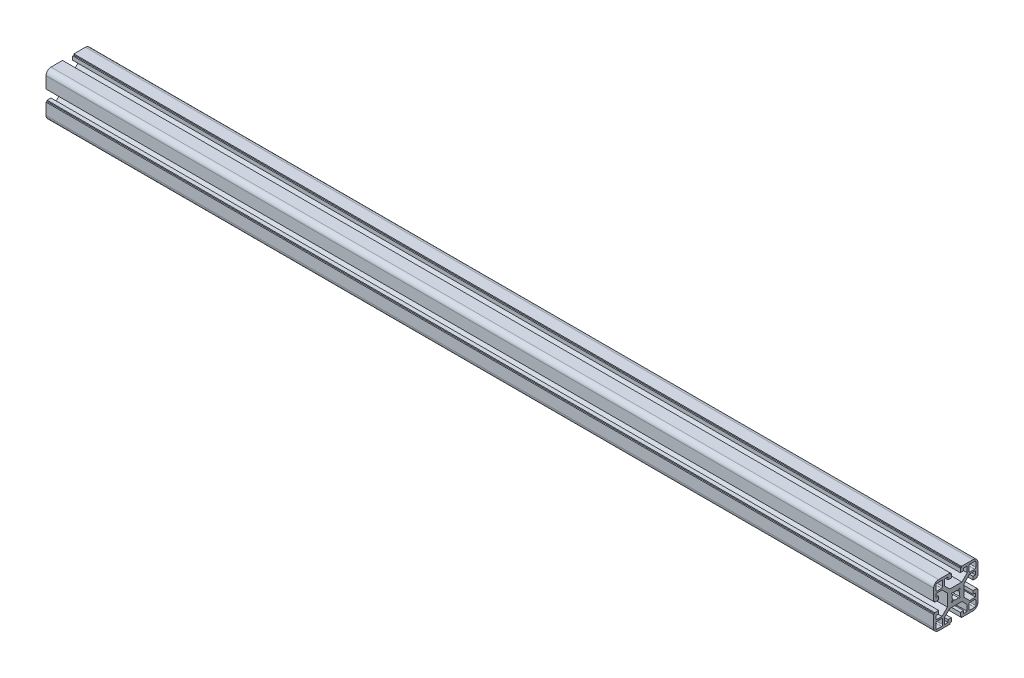
SolidWorks part; units mm, degrees
ref_plane "前视基准面" through (0, 0, 0) normal (0, 0, 1) x (1, 0, 0)
ref_plane "上视基准面" through (0, 0, 0) normal (0, 1, 0) x (1, 0, 0)
ref_plane "右视基准面" through (0, 0, 0) normal (1, 0, 0) x (0, 0, -1)
other "Configuration Table"
sketch "草图1" plane through (0, 0, 0) normal (1, 0, 0) x (0, 0, -1)
  line L0 (4.82, 19.28) -> (3.82, 19.28)
  line L1 (3.82, 19.28) -> (3.82, 15.78)
  line L2 (3.82, 15.78) -> (6.7364, 15.78)
  line L3 (6.7364, 15.78) -> (6.7364, 18.03)
  line L4 (6.7364, 18.03) -> (10.02, 18.03)
  line L5 (10.02, 18.03) -> (10.02, 12.7013)
  line L6 (10.02, 12.7013) -> (5.1987, 7.88)
  line L7 (5.1987, 7.88) -> (-5.7586, 7.88)
  line L8 (-5.7586, 7.88) -> (-10.58, 12.7013)
  line L9 (-10.58, 12.7013) -> (-10.58, 18.03)
  line L10 (-10.58, 18.03) -> (-7.2963, 18.03)
  line L11 (-7.2963, 18.03) -> (-7.2963, 15.78)
  line L12 (-7.2963, 15.78) -> (-4.38, 15.78)
  line L13 (-4.38, 15.78) -> (-4.38, 19.28)
  line L14 (-4.38, 19.28) -> (-5.38, 19.28)
  line L15 (-5.38, 19.28) -> (-5.38, 20.28)
  line L16 (-5.38, 20.28) -> (-15.78, 20.28)
  line L17 (-20.28, 15.78) -> (-20.28, 5.38)
  line L18 (-20.28, 5.38) -> (-19.28, 5.38)
  line L19 (-19.28, 5.38) -> (-19.28, 4.38)
  line L20 (-19.28, 4.38) -> (-15.78, 4.38)
  line L21 (-15.78, 4.38) -> (-15.78, 7.2963)
  line L22 (-15.78, 7.2963) -> (-18.03, 7.2963)
  line L23 (-18.03, 7.2963) -> (-18.03, 10.58)
  line L24 (-18.03, 10.58) -> (-12.7013, 10.58)
  line L25 (-12.7013, 10.58) -> (-7.88, 5.7586)
  line L26 (-7.88, 5.7586) -> (-7.88, -5.1987)
  line L27 (-7.88, -5.1987) -> (-12.7013, -10.02)
  line L28 (-12.7013, -10.02) -> (-18.03, -10.02)
  line L29 (-18.03, -10.02) -> (-18.03, -6.7364)
  line L30 (-18.03, -6.7364) -> (-15.78, -6.7364)
  line L31 (-15.78, -6.7364) -> (-15.78, -3.82)
  line L32 (-15.78, -3.82) -> (-19.28, -3.82)
  line L33 (-19.28, -3.82) -> (-19.28, -4.82)
  line L34 (-19.28, -4.82) -> (-20.28, -4.82)
  line L35 (-20.28, -4.82) -> (-20.28, -15.22)
  line L36 (-15.78, -19.72) -> (-5.38, -19.72)
  line L37 (-5.38, -19.72) -> (-5.38, -18.72)
  line L38 (-5.38, -18.72) -> (-4.38, -18.72)
  line L39 (-4.38, -18.72) -> (-4.38, -15.22)
  line L40 (-4.38, -15.22) -> (-7.2963, -15.22)
  line L41 (-7.2963, -15.22) -> (-7.2963, -17.47)
  line L42 (-7.2963, -17.47) -> (-10.58, -17.47)
  line L43 (-10.58, -17.47) -> (-10.58, -12.1414)
  line L44 (-10.58, -12.1414) -> (-5.7586, -7.32)
  line L45 (-5.7586, -7.32) -> (5.1987, -7.32)
  line L46 (5.1987, -7.32) -> (10.02, -12.1414)
  line L47 (10.02, -12.1414) -> (10.02, -17.47)
  line L48 (10.02, -17.47) -> (6.7364, -17.47)
  line L49 (6.7364, -17.47) -> (6.7364, -15.22)
  line L50 (6.7364, -15.22) -> (3.82, -15.22)
  line L51 (3.82, -15.22) -> (3.82, -18.72)
  line L52 (3.82, -18.72) -> (4.82, -18.72)
  line L53 (4.82, -18.72) -> (4.82, -19.72)
  line L54 (4.82, -19.72) -> (15.22, -19.72)
  line L55 (19.72, -15.22) -> (19.72, -4.82)
  line L56 (19.72, -4.82) -> (18.72, -4.82)
  line L57 (18.72, -4.82) -> (18.72, -3.82)
  line L58 (18.72, -3.82) -> (15.22, -3.82)
  line L59 (15.22, -3.82) -> (15.22, -6.7364)
  line L60 (15.22, -6.7364) -> (17.47, -6.7364)
  line L61 (17.47, -6.7364) -> (17.47, -10.02)
  line L62 (17.47, -10.02) -> (12.1414, -10.02)
  line L63 (12.1414, -10.02) -> (7.32, -5.1987)
  line L64 (7.32, -5.1987) -> (7.32, 5.7586)
  line L65 (7.32, 5.7586) -> (12.1414, 10.58)
  line L66 (12.1414, 10.58) -> (17.47, 10.58)
  line L67 (17.47, 10.58) -> (17.47, 7.2963)
  line L68 (17.47, 7.2963) -> (15.22, 7.2963)
  line L69 (15.22, 7.2963) -> (15.22, 4.38)
  line L70 (15.22, 4.38) -> (18.72, 4.38)
  line L71 (18.72, 4.38) -> (18.72, 5.38)
  line L72 (18.72, 5.38) -> (19.72, 5.38)
  line L73 (19.72, 5.38) -> (19.72, 15.78)
  line L74 (15.22, 20.28) -> (4.82, 20.28)
  line L75 (4.82, 20.28) -> (4.82, 19.28)
  line L76 (-13.08, -17.72) -> (-17.28, -17.72)
  line L77 (-18.28, -16.72) -> (-18.28, -12.52)
  line L78 (-17.28, -11.52) -> (-13.08, -11.52)
  line L79 (-12.08, -12.52) -> (-12.08, -16.72)
  line L80 (-17.28, 18.28) -> (-13.08, 18.28)
  line L81 (-12.08, 17.28) -> (-12.08, 13.08)
  line L82 (-13.08, 12.08) -> (-17.28, 12.08)
  line L83 (-18.28, 13.08) -> (-18.28, 17.28)
  line L84 (16.72, 12.08) -> (12.52, 12.08)
  line L85 (11.52, 13.08) -> (11.52, 17.28)
  line L86 (12.52, 18.28) -> (16.72, 18.28)
  line L87 (17.72, 17.28) -> (17.72, 13.08)
  line L88 (3.7505, -3.0434) -> (3.0434, -3.7505)
  line L89 (3.0434, -3.7505) -> (1.7445, -2.4516)
  line L90 (-2.3044, -2.4516) -> (-3.6033, -3.7505)
  line L91 (-3.6033, -3.7505) -> (-4.3104, -3.0434)
  line L92 (-4.3104, -3.0434) -> (-3.0115, -1.7445)
  line L93 (-3.0115, 2.3044) -> (-4.3104, 3.6033)
  line L94 (-4.3104, 3.6033) -> (-3.6033, 4.3104)
  line L95 (-3.6033, 4.3104) -> (-2.3044, 3.0115)
  line L96 (1.7445, 3.0115) -> (3.0434, 4.3104)
  line L97 (3.0434, 4.3104) -> (3.7505, 3.6033)
  line L98 (3.7505, 3.6033) -> (2.4516, 2.3044)
  line L99 (2.4516, -1.7445) -> (3.7505, -3.0434)
  line L100 (17.72, -12.52) -> (17.72, -16.72)
  line L101 (16.72, -17.72) -> (12.52, -17.72)
  line L102 (11.52, -16.72) -> (11.52, -12.52)
  line L103 (12.52, -11.52) -> (16.72, -11.52)
  arc A0 (-15.78, 20.28) -> (-20.28, 15.78) centre (-15.78, 15.78) ccw
  arc A1 (-20.28, -15.22) -> (-15.78, -19.72) centre (-15.78, -15.22) ccw
  arc A2 (15.22, -19.72) -> (19.72, -15.22) centre (15.22, -15.22) ccw
  arc A3 (19.72, 15.78) -> (15.22, 20.28) centre (15.22, 15.78) ccw
  arc A4 (-12.08, -16.72) -> (-13.08, -17.72) centre (-13.08, -16.72) cw
  arc A5 (-17.28, -17.72) -> (-18.28, -16.72) centre (-17.28, -16.72) cw
  arc A6 (-18.28, -12.52) -> (-17.28, -11.52) centre (-17.28, -12.52) cw
  arc A7 (-13.08, -11.52) -> (-12.08, -12.52) centre (-13.08, -12.52) cw
  arc A8 (-18.28, 17.28) -> (-17.28, 18.28) centre (-17.28, 17.28) cw
  arc A9 (-13.08, 18.28) -> (-12.08, 17.28) centre (-13.08, 17.28) cw
  arc A10 (-12.08, 13.08) -> (-13.08, 12.08) centre (-13.08, 13.08) cw
  arc A11 (-17.28, 12.08) -> (-18.28, 13.08) centre (-17.28, 13.08) cw
  arc A12 (17.72, 13.08) -> (16.72, 12.08) centre (16.72, 13.08) cw
  arc A13 (12.52, 12.08) -> (11.52, 13.08) centre (12.52, 13.08) cw
  arc A14 (11.52, 17.28) -> (12.52, 18.28) centre (12.52, 17.28) cw
  arc A15 (16.72, 18.28) -> (17.72, 17.28) centre (16.72, 17.28) cw
  arc A16 (1.7445, -2.4516) -> (-2.3044, -2.4516) centre (-0.28, 0.28) cw
  arc A17 (-3.0115, -1.7445) -> (-3.0115, 2.3044) centre (-0.28, 0.28) cw
  arc A18 (-2.3044, 3.0115) -> (1.7445, 3.0115) centre (-0.28, 0.28) cw
  arc A19 (2.4516, 2.3044) -> (2.4516, -1.7445) centre (-0.28, 0.28) cw
  arc A20 (16.72, -11.52) -> (17.72, -12.52) centre (16.72, -12.52) cw
  arc A21 (17.72, -16.72) -> (16.72, -17.72) centre (16.72, -16.72) cw
  arc A22 (12.52, -17.72) -> (11.52, -16.72) centre (12.52, -16.72) cw
  arc A23 (11.52, -12.52) -> (12.52, -11.52) centre (12.52, -12.52) cw
extrude "凸台-拉伸1" add sketch "草图1" against normal blind 50
sketch "草图2" plane through (0, 0, 0) normal (1, 0, 0) x (0, 0, -1)
  line L4 (-17.28, -17.72) -> (-13.08, -17.72)
  line L5 (-18.28, -12.52) -> (-18.28, -16.72)
  line L6 (-13.08, -11.52) -> (-17.28, -11.52)
  line L7 (-12.08, -16.72) -> (-12.08, -12.52)
  line L8 (-17.28, -17.72) -> (-13.08, -17.72)
  line L9 (-18.28, -12.52) -> (-18.28, -16.72)
  line L10 (-13.08, -11.52) -> (-17.28, -11.52)
  line L11 (-12.08, -16.72) -> (-12.08, -12.52)
  line L12 (-13.08, 18.28) -> (-17.28, 18.28)
  line L13 (-12.08, 13.08) -> (-12.08, 17.28)
  line L14 (-17.28, 12.08) -> (-13.08, 12.08)
  line L15 (-18.28, 17.28) -> (-18.28, 13.08)
  line L16 (-13.08, 18.28) -> (-17.28, 18.28)
  line L17 (-12.08, 13.08) -> (-12.08, 17.28)
  line L18 (-17.28, 12.08) -> (-13.08, 12.08)
  line L19 (-18.28, 17.28) -> (-18.28, 13.08)
  line L20 (11.52, 17.28) -> (11.52, 13.08)
  line L21 (16.72, 18.28) -> (12.52, 18.28)
  line L22 (17.72, 13.08) -> (17.72, 17.28)
  line L23 (12.52, 12.08) -> (16.72, 12.08)
  line L24 (11.52, 17.28) -> (11.52, 13.08)
  line L25 (16.72, 18.28) -> (12.52, 18.28)
  line L26 (17.72, 13.08) -> (17.72, 17.28)
  line L27 (12.52, 12.08) -> (16.72, 12.08)
  line L28 (11.52, -12.52) -> (11.52, -16.72)
  line L29 (16.72, -11.52) -> (12.52, -11.52)
  line L30 (17.72, -16.72) -> (17.72, -12.52)
  line L31 (12.52, -17.72) -> (16.72, -17.72)
  line L32 (11.52, -12.52) -> (11.52, -16.72)
  line L33 (16.72, -11.52) -> (12.52, -11.52)
  line L34 (17.72, -16.72) -> (17.72, -12.52)
  line L35 (12.52, -17.72) -> (16.72, -17.72)
  line L36 (-4.3104, 3.6033) -> (-3.0115, 2.3044)
  line L37 (-3.6033, 4.3104) -> (-4.3104, 3.6033)
  line L38 (-2.3044, 3.0115) -> (-3.6033, 4.3104)
  line L39 (3.0434, 4.3104) -> (1.7445, 3.0115)
  line L40 (3.7505, 3.6033) -> (3.0434, 4.3104)
  line L41 (2.4516, 2.3044) -> (3.7505, 3.6033)
  line L42 (3.7505, -3.0434) -> (2.4516, -1.7445)
  line L43 (3.0434, -3.7505) -> (3.7505, -3.0434)
  line L44 (1.7445, -2.4516) -> (3.0434, -3.7505)
  line L45 (-3.6033, -3.7505) -> (-2.3044, -2.4516)
  line L46 (-4.3104, -3.0434) -> (-3.6033, -3.7505)
  line L47 (-3.0115, -1.7445) -> (-4.3104, -3.0434)
  line L48 (-4.3104, 3.6033) -> (-3.0115, 2.3044)
  line L49 (-3.6033, 4.3104) -> (-4.3104, 3.6033)
  line L50 (-2.3044, 3.0115) -> (-3.6033, 4.3104)
  line L51 (3.0434, 4.3104) -> (1.7445, 3.0115)
  line L52 (3.7505, 3.6033) -> (3.0434, 4.3104)
  line L53 (2.4516, 2.3044) -> (3.7505, 3.6033)
  line L54 (3.7505, -3.0434) -> (2.4516, -1.7445)
  line L55 (3.0434, -3.7505) -> (3.7505, -3.0434)
  line L56 (1.7445, -2.4516) -> (3.0434, -3.7505)
  line L57 (-3.6033, -3.7505) -> (-2.3044, -2.4516)
  line L58 (-4.3104, -3.0434) -> (-3.6033, -3.7505)
  line L59 (-3.0115, -1.7445) -> (-4.3104, -3.0434)
  line L84 (19.72, 5.38) -> (19.72, 15.78)
  line L85 (18.72, 5.38) -> (19.72, 5.38)
  line L86 (18.72, 4.38) -> (18.72, 5.38)
  line L87 (15.22, 4.38) -> (18.72, 4.38)
  line L88 (15.22, 7.2963) -> (15.22, 4.38)
  line L89 (17.47, 7.2963) -> (15.22, 7.2963)
  line L90 (17.47, 10.58) -> (17.47, 7.2963)
  line L91 (12.1414, 10.58) -> (17.47, 10.58)
  line L92 (7.32, 5.7586) -> (12.1414, 10.58)
  line L93 (7.32, -5.1987) -> (7.32, 5.7586)
  line L94 (12.1414, -10.02) -> (7.32, -5.1987)
  line L95 (17.47, -10.02) -> (12.1414, -10.02)
  line L96 (17.47, -6.7364) -> (17.47, -10.02)
  line L97 (15.22, -6.7364) -> (17.47, -6.7364)
  line L98 (15.22, -3.82) -> (15.22, -6.7364)
  line L99 (18.72, -3.82) -> (15.22, -3.82)
  line L100 (18.72, -4.82) -> (18.72, -3.82)
  line L101 (19.72, -4.82) -> (18.72, -4.82)
  line L102 (19.72, -15.22) -> (19.72, -4.82)
  line L103 (4.82, -19.72) -> (15.22, -19.72)
  line L104 (4.82, -18.72) -> (4.82, -19.72)
  line L105 (3.82, -18.72) -> (4.82, -18.72)
  line L106 (3.82, -15.22) -> (3.82, -18.72)
  line L107 (6.7364, -15.22) -> (3.82, -15.22)
  line L108 (6.7364, -17.47) -> (6.7364, -15.22)
  line L109 (10.02, -17.47) -> (6.7364, -17.47)
  line L110 (10.02, -12.1414) -> (10.02, -17.47)
  line L111 (5.1987, -7.32) -> (10.02, -12.1414)
  line L112 (-5.7586, -7.32) -> (5.1987, -7.32)
  line L113 (-10.58, -12.1414) -> (-5.7586, -7.32)
  line L114 (-10.58, -17.47) -> (-10.58, -12.1414)
  line L115 (-7.2963, -17.47) -> (-10.58, -17.47)
  line L116 (-7.2963, -15.22) -> (-7.2963, -17.47)
  line L117 (-4.38, -15.22) -> (-7.2963, -15.22)
  line L118 (-4.38, -18.72) -> (-4.38, -15.22)
  line L119 (-5.38, -18.72) -> (-4.38, -18.72)
  line L120 (-5.38, -19.72) -> (-5.38, -18.72)
  line L121 (-15.78, -19.72) -> (-5.38, -19.72)
  line L122 (-20.28, -4.82) -> (-20.28, -15.22)
  line L123 (-19.28, -4.82) -> (-20.28, -4.82)
  line L124 (-19.28, -3.82) -> (-19.28, -4.82)
  line L125 (-15.78, -3.82) -> (-19.28, -3.82)
  line L126 (-15.78, -6.7364) -> (-15.78, -3.82)
  line L127 (-18.03, -6.7364) -> (-15.78, -6.7364)
  line L128 (-18.03, -10.02) -> (-18.03, -6.7364)
  line L129 (-12.7013, -10.02) -> (-18.03, -10.02)
  line L130 (-7.88, -5.1987) -> (-12.7013, -10.02)
  line L131 (-7.88, 5.7586) -> (-7.88, -5.1987)
  line L132 (-12.7013, 10.58) -> (-7.88, 5.7586)
  line L133 (-18.03, 10.58) -> (-12.7013, 10.58)
  line L134 (-18.03, 7.2963) -> (-18.03, 10.58)
  line L135 (-15.78, 7.2963) -> (-18.03, 7.2963)
  line L136 (-15.78, 4.38) -> (-15.78, 7.2963)
  line L137 (-19.28, 4.38) -> (-15.78, 4.38)
  line L138 (-19.28, 5.38) -> (-19.28, 4.38)
  line L139 (-20.28, 5.38) -> (-19.28, 5.38)
  line L140 (-20.28, 15.78) -> (-20.28, 5.38)
  line L141 (-5.38, 20.28) -> (-15.78, 20.28)
  line L142 (-5.38, 19.28) -> (-5.38, 20.28)
  line L143 (-4.38, 19.28) -> (-5.38, 19.28)
  line L144 (-4.38, 15.78) -> (-4.38, 19.28)
  line L145 (-7.2963, 15.78) -> (-4.38, 15.78)
  line L146 (-7.2963, 18.03) -> (-7.2963, 15.78)
  line L147 (-10.58, 18.03) -> (-7.2963, 18.03)
  line L148 (-10.58, 12.7013) -> (-10.58, 18.03)
  line L149 (-5.7586, 7.88) -> (-10.58, 12.7013)
  line L150 (5.1987, 7.88) -> (-5.7586, 7.88)
  line L151 (10.02, 12.7013) -> (5.1987, 7.88)
  line L152 (10.02, 18.03) -> (10.02, 12.7013)
  line L153 (6.7364, 18.03) -> (10.02, 18.03)
  line L154 (6.7364, 15.78) -> (6.7364, 18.03)
  line L155 (3.82, 15.78) -> (6.7364, 15.78)
  line L156 (3.82, 19.28) -> (3.82, 15.78)
  line L157 (4.82, 19.28) -> (3.82, 19.28)
  line L158 (4.82, 20.28) -> (4.82, 19.28)
  line L159 (15.22, 20.28) -> (4.82, 20.28)
  line L160 (19.72, 5.38) -> (19.72, 15.78)
  line L161 (18.72, 5.38) -> (19.72, 5.38)
  line L162 (18.72, 4.38) -> (18.72, 5.38)
  line L163 (15.22, 4.38) -> (18.72, 4.38)
  line L164 (15.22, 7.2963) -> (15.22, 4.38)
  line L165 (17.47, 7.2963) -> (15.22, 7.2963)
  line L166 (17.47, 10.58) -> (17.47, 7.2963)
  line L167 (12.1414, 10.58) -> (17.47, 10.58)
  line L168 (7.32, 5.7586) -> (12.1414, 10.58)
  line L169 (7.32, -5.1987) -> (7.32, 5.7586)
  line L170 (12.1414, -10.02) -> (7.32, -5.1987)
  line L171 (17.47, -10.02) -> (12.1414, -10.02)
  line L172 (17.47, -6.7364) -> (17.47, -10.02)
  line L173 (15.22, -6.7364) -> (17.47, -6.7364)
  line L174 (15.22, -3.82) -> (15.22, -6.7364)
  line L175 (18.72, -3.82) -> (15.22, -3.82)
  line L176 (18.72, -4.82) -> (18.72, -3.82)
  line L177 (19.72, -4.82) -> (18.72, -4.82)
  line L178 (19.72, -15.22) -> (19.72, -4.82)
  line L179 (4.82, -19.72) -> (15.22, -19.72)
  line L180 (4.82, -18.72) -> (4.82, -19.72)
  line L181 (3.82, -18.72) -> (4.82, -18.72)
  line L182 (3.82, -15.22) -> (3.82, -18.72)
  line L183 (6.7364, -15.22) -> (3.82, -15.22)
  line L184 (6.7364, -17.47) -> (6.7364, -15.22)
  line L185 (10.02, -17.47) -> (6.7364, -17.47)
  line L186 (10.02, -12.1414) -> (10.02, -17.47)
  line L187 (5.1987, -7.32) -> (10.02, -12.1414)
  line L188 (-5.7586, -7.32) -> (5.1987, -7.32)
  line L189 (-10.58, -12.1414) -> (-5.7586, -7.32)
  line L190 (-10.58, -17.47) -> (-10.58, -12.1414)
  line L191 (-7.2963, -17.47) -> (-10.58, -17.47)
  line L192 (-7.2963, -15.22) -> (-7.2963, -17.47)
  line L193 (-4.38, -15.22) -> (-7.2963, -15.22)
  line L194 (-4.38, -18.72) -> (-4.38, -15.22)
  line L195 (-5.38, -18.72) -> (-4.38, -18.72)
  line L196 (-5.38, -19.72) -> (-5.38, -18.72)
  line L197 (-15.78, -19.72) -> (-5.38, -19.72)
  line L198 (-20.28, -4.82) -> (-20.28, -15.22)
  line L199 (-19.28, -4.82) -> (-20.28, -4.82)
  line L200 (-19.28, -3.82) -> (-19.28, -4.82)
  line L201 (-15.78, -3.82) -> (-19.28, -3.82)
  line L202 (-15.78, -6.7364) -> (-15.78, -3.82)
  line L203 (-18.03, -6.7364) -> (-15.78, -6.7364)
  line L204 (-18.03, -10.02) -> (-18.03, -6.7364)
  line L205 (-12.7013, -10.02) -> (-18.03, -10.02)
  line L206 (-7.88, -5.1987) -> (-12.7013, -10.02)
  line L207 (-7.88, 5.7586) -> (-7.88, -5.1987)
  line L208 (-12.7013, 10.58) -> (-7.88, 5.7586)
  line L209 (-18.03, 10.58) -> (-12.7013, 10.58)
  line L210 (-18.03, 7.2963) -> (-18.03, 10.58)
  line L211 (-15.78, 7.2963) -> (-18.03, 7.2963)
  line L212 (-15.78, 4.38) -> (-15.78, 7.2963)
  line L213 (-19.28, 4.38) -> (-15.78, 4.38)
  line L214 (-19.28, 5.38) -> (-19.28, 4.38)
  line L215 (-20.28, 5.38) -> (-19.28, 5.38)
  line L216 (-20.28, 15.78) -> (-20.28, 5.38)
  line L217 (-5.38, 20.28) -> (-15.78, 20.28)
  line L218 (-5.38, 19.28) -> (-5.38, 20.28)
  line L219 (-4.38, 19.28) -> (-5.38, 19.28)
  line L220 (-4.38, 15.78) -> (-4.38, 19.28)
  line L221 (-7.2963, 15.78) -> (-4.38, 15.78)
  line L222 (-7.2963, 18.03) -> (-7.2963, 15.78)
  line L223 (-10.58, 18.03) -> (-7.2963, 18.03)
  line L224 (-10.58, 12.7013) -> (-10.58, 18.03)
  line L225 (-5.7586, 7.88) -> (-10.58, 12.7013)
  line L226 (5.1987, 7.88) -> (-5.7586, 7.88)
  line L227 (10.02, 12.7013) -> (5.1987, 7.88)
  line L228 (10.02, 18.03) -> (10.02, 12.7013)
  line L229 (6.7364, 18.03) -> (10.02, 18.03)
  line L230 (6.7364, 15.78) -> (6.7364, 18.03)
  line L231 (3.82, 15.78) -> (6.7364, 15.78)
  line L232 (3.82, 19.28) -> (3.82, 15.78)
  line L233 (4.82, 19.28) -> (3.82, 19.28)
  line L234 (4.82, 20.28) -> (4.82, 19.28)
  line L235 (15.22, 20.28) -> (4.82, 20.28)
  arc A4 (-18.28, -16.72) -> (-17.28, -17.72) centre (-17.28, -16.72) ccw
  arc A5 (-17.28, -11.52) -> (-18.28, -12.52) centre (-17.28, -12.52) ccw
  arc A6 (-12.08, -12.52) -> (-13.08, -11.52) centre (-13.08, -12.52) ccw
  arc A7 (-13.08, -17.72) -> (-12.08, -16.72) centre (-13.08, -16.72) ccw
  arc A8 (-18.28, -16.72) -> (-17.28, -17.72) centre (-17.28, -16.72) ccw
  arc A9 (-17.28, -11.52) -> (-18.28, -12.52) centre (-17.28, -12.52) ccw
  arc A10 (-12.08, -12.52) -> (-13.08, -11.52) centre (-13.08, -12.52) ccw
  arc A11 (-13.08, -17.72) -> (-12.08, -16.72) centre (-13.08, -16.72) ccw
  arc A12 (15.22, -19.72) -> (19.72, -15.22) centre (15.22, -15.22) ccw
  arc A13 (-20.28, -15.22) -> (-15.78, -19.72) centre (-15.78, -15.22) ccw
  arc A14 (-15.78, 20.28) -> (-20.28, 15.78) centre (-15.78, 15.78) ccw
  arc A15 (19.72, 15.78) -> (15.22, 20.28) centre (15.22, 15.78) ccw
  arc A16 (15.22, -19.72) -> (19.72, -15.22) centre (15.22, -15.22) ccw
  arc A17 (-20.28, -15.22) -> (-15.78, -19.72) centre (-15.78, -15.22) ccw
  arc A18 (-15.78, 20.28) -> (-20.28, 15.78) centre (-15.78, 15.78) ccw
  arc A19 (19.72, 15.78) -> (15.22, 20.28) centre (15.22, 15.78) ccw
  arc A20 (-12.08, 17.28) -> (-13.08, 18.28) centre (-13.08, 17.28) ccw
  arc A21 (-13.08, 12.08) -> (-12.08, 13.08) centre (-13.08, 13.08) ccw
  arc A22 (-18.28, 13.08) -> (-17.28, 12.08) centre (-17.28, 13.08) ccw
  arc A23 (-17.28, 18.28) -> (-18.28, 17.28) centre (-17.28, 17.28) ccw
  arc A24 (-12.08, 17.28) -> (-13.08, 18.28) centre (-13.08, 17.28) ccw
  arc A25 (-13.08, 12.08) -> (-12.08, 13.08) centre (-13.08, 13.08) ccw
  arc A26 (-18.28, 13.08) -> (-17.28, 12.08) centre (-17.28, 13.08) ccw
  arc A27 (-17.28, 18.28) -> (-18.28, 17.28) centre (-17.28, 17.28) ccw
  arc A28 (12.52, 18.28) -> (11.52, 17.28) centre (12.52, 17.28) ccw
  arc A29 (17.72, 17.28) -> (16.72, 18.28) centre (16.72, 17.28) ccw
  arc A30 (16.72, 12.08) -> (17.72, 13.08) centre (16.72, 13.08) ccw
  arc A31 (11.52, 13.08) -> (12.52, 12.08) centre (12.52, 13.08) ccw
  arc A32 (12.52, 18.28) -> (11.52, 17.28) centre (12.52, 17.28) ccw
  arc A33 (17.72, 17.28) -> (16.72, 18.28) centre (16.72, 17.28) ccw
  arc A34 (16.72, 12.08) -> (17.72, 13.08) centre (16.72, 13.08) ccw
  arc A35 (11.52, 13.08) -> (12.52, 12.08) centre (12.52, 13.08) ccw
  arc A36 (1.7445, 3.0115) -> (-2.3044, 3.0115) centre (-0.28, 0.28) ccw
  arc A37 (2.4516, -1.7445) -> (2.4516, 2.3044) centre (-0.28, 0.28) ccw
  arc A38 (-2.3044, -2.4516) -> (1.7445, -2.4516) centre (-0.28, 0.28) ccw
  arc A39 (-3.0115, 2.3044) -> (-3.0115, -1.7445) centre (-0.28, 0.28) ccw
  arc A40 (1.7445, 3.0115) -> (-2.3044, 3.0115) centre (-0.28, 0.28) ccw
  arc A41 (2.4516, -1.7445) -> (2.4516, 2.3044) centre (-0.28, 0.28) ccw
  arc A42 (-2.3044, -2.4516) -> (1.7445, -2.4516) centre (-0.28, 0.28) ccw
  arc A43 (-3.0115, 2.3044) -> (-3.0115, -1.7445) centre (-0.28, 0.28) ccw
  arc A44 (12.52, -11.52) -> (11.52, -12.52) centre (12.52, -12.52) ccw
  arc A45 (17.72, -12.52) -> (16.72, -11.52) centre (16.72, -12.52) ccw
  arc A46 (16.72, -17.72) -> (17.72, -16.72) centre (16.72, -16.72) ccw
  arc A47 (11.52, -16.72) -> (12.52, -17.72) centre (12.52, -16.72) ccw
  arc A48 (12.52, -11.52) -> (11.52, -12.52) centre (12.52, -12.52) ccw
  arc A49 (17.72, -12.52) -> (16.72, -11.52) centre (16.72, -12.52) ccw
  arc A50 (16.72, -17.72) -> (17.72, -16.72) centre (16.72, -16.72) ccw
  arc A51 (11.52, -16.72) -> (12.52, -17.72) centre (12.52, -16.72) ccw
  dimension "D1" = 0
  dimension "D2" = 0
  dimension "D3" = 0
  dimension "D4" = 0
  dimension "D5" = 0
  dimension "D6" = 0
extrude "凸台-拉伸2" add sketch "草图2" against normal blind 800
sketch "草图3" plane through (0, 0, 0) normal (0, 0, 1) x (1, 0, 0)
  line L0 (-800, 5.38) -> (-800, -4.82) construction
  line L1 (-1800, 0.28) -> (48200, 0.28) construction
  line L2 (-400, -996.469) -> (-400, 49003.531) construction
  line L3 (-475, 0.28) -> (-325, 0.28) construction
  line L4 (-371, 0.28) -> (-279, 0.28) construction
  line L5 (-475, 0.2799) -> (-475, 0.2801) construction
  circle A0 centre (-371, 0.28) radius 3
  circle A1 centre (-279, 0.28) radius 3
  circle A2 centre (-521, 0.28) radius 3
  circle A3 centre (-429, 0.28) radius 3
  point P7 (-800, 0.28)
  point P12 (-400, 0.28)
  point P16 (-325, 0.28)
  point P29 (-475, 0.28)
  dimension "D4" = 6
  dimension "D5" = 6
  dimension "D1" = 400
  dimension "D2" = 150
  dimension "D3" = 92
extrude "切除-拉伸1" cut sketch "草图3" along normal up to surface (40 mm away) from surface at -19.72 up to face at (-400, -10.02, 20.28) starting at face at (-400, -10.02, -19.72)
